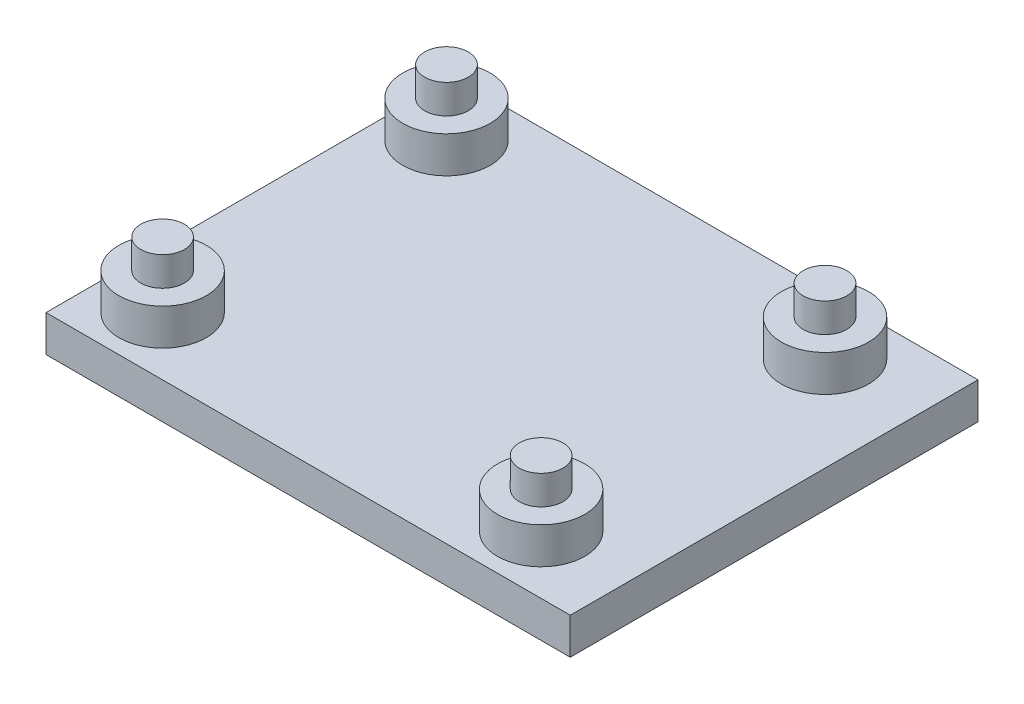
SolidWorks part; units mm, degrees
ref_plane "Front Plane" through (0, 0, 0) normal (0, 0, 1) x (1, 0, 0)
ref_plane "Top Plane" through (0, 0, 0) normal (0, 1, 0) x (1, 0, 0)
ref_plane "Right Plane" through (0, 0, 0) normal (1, 0, 0) x (0, 0, -1)
sketch "Sketch1" plane through (0, 0, 0) normal (0, 1, 0) x (1, 0, 0)
  line L1 (-18, -14) -> (18, -14)
  line L2 (-18, -14) -> (-18, 14)
  line L3 (-18, 14) -> (18, 14)
  line L4 (18, -14) -> (18, 14)
  line L5 (-18, -14) -> (18, 14) construction
  line L6 (-18, 14) -> (18, -14) construction
  point P0 (0, 0)
  dimension "D1" = 36
  dimension "D2" = 28
extrude "Boss-Extrude1" add sketch "Sketch1" along normal blind 5
sketch "Sketch2" plane through (0, 5, 0) normal (0, 1, 0) x (1, 0, 0)
  circle A0 centre (-14.5, 10) radius 1.5
  circle A1 centre (-14, -9.9937) radius 1.5
  circle A2 centre (12, -10) radius 1.5
  circle A3 centre (11.5, 9.9937) radius 1.5
  dimension "D1" = 3
  dimension "D2" = 3
  dimension "D3" = 3
  dimension "D12" = 3
  dimension "D4" = 20
  dimension "D5" = 14
  dimension "D6" = 12
  dimension "D7" = 20
  dimension "D8" = 26
extrude "Boss-Extrude2" add sketch "Sketch2" along normal blind 2
sketch "Sketch3" plane through (0, 5, 0) normal (0, 1, 0) x (1, 0, 0)
  circle A0 centre (-14.5, 10) radius 3
  circle A1 centre (-14.5, 10) radius 1.5 construction
  circle A2 centre (-14, -9.9937) radius 3
  circle A3 centre (12, -10) radius 3
  circle A4 centre (11.5, 9.9937) radius 3
  circle A5 centre (-14, -9.9937) radius 1.5 construction
  circle A6 centre (12, -10) radius 1.5 construction
  circle A7 centre (11.5, 9.9937) radius 1.5 construction
  line M5 (18, -14) -> (18, 14)
  line M6 (18, 14) -> (-18, 14)
  line M7 (-18, 14) -> (-18, -14)
  line M8 (-18, -14) -> (18, -14)
  dimension "D1" = 1.5
  dimension "D2" = 1.5
  dimension "D3" = 1.5
  dimension "D4" = 1.5
extrude "Cut-Extrude3" cut sketch "Sketch3" against normal blind 2.5 contours A4 A3 A2 A0 M8 M5 M6 M7
